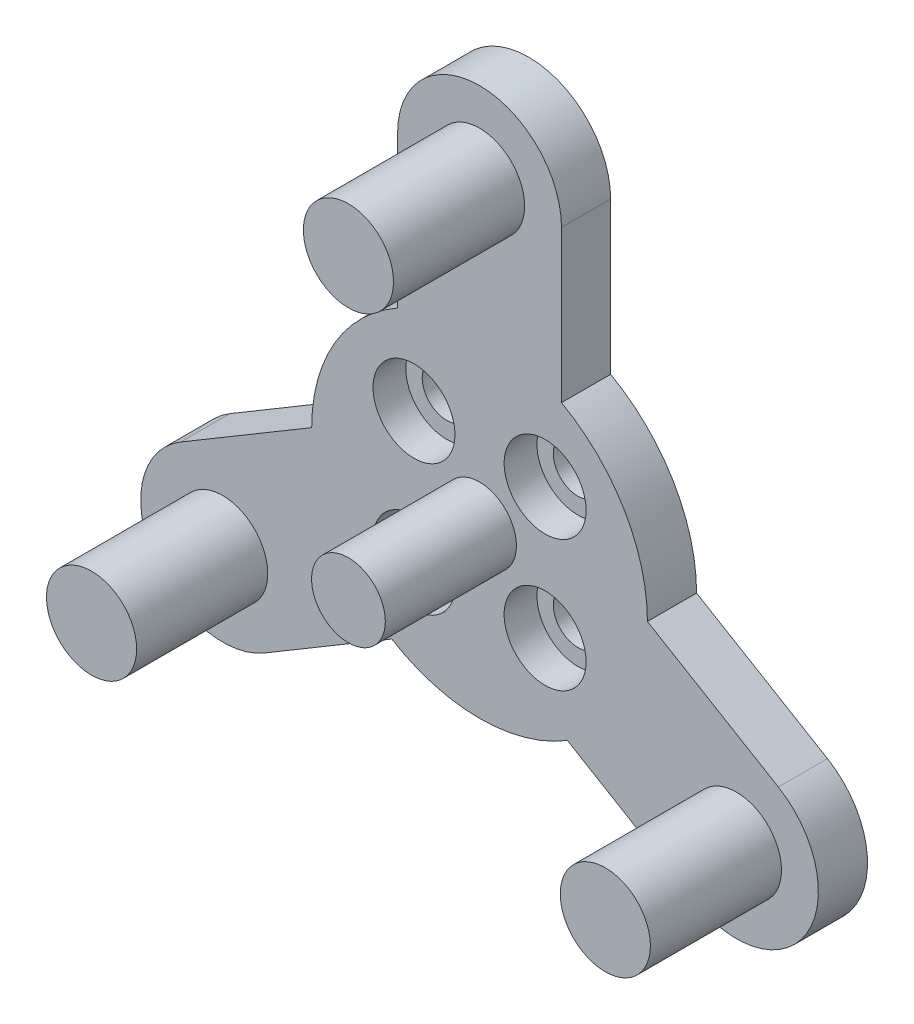
SolidWorks part; units mm, degrees
ref_plane "Alzado" through (0, 0, 0) normal (0, 0, 1) x (1, 0, 0)
ref_plane "Planta" through (0, 0, 0) normal (0, 1, 0) x (1, 0, 0)
ref_plane "Vista lateral" through (0, 0, 0) normal (1, 0, 0) x (0, 0, -1)
sketch "Croquis1" plane through (0, 0, 0) normal (0, 0, 1) x (1, 0, 0)
  line L0 (-18.2318, -4.7531) -> (-10.2435, 0)
  line L1 (-13.1183, -13.3469) -> (-5.359, -8.7299)
  line L2 (13.1183, -13.3469) -> (5.359, -8.7299)
  line L3 (-13.1183, -13.3469) -> (-18.2318, -4.7531)
  line L7 (13.1183, -13.3469) -> (18.2318, -4.7531)
  line L11 (-5, 18.2) -> (5, 18.2)
  line L15 (18.2318, -4.7531) -> (10.2435, 0)
  line L16 (-5, 18.2) -> (-5, 8.9404)
  line L17 (5, 18.2) -> (5, 8.9404)
  circle A0 centre (0, 18.2) radius 5
  circle A1 centre (15.6751, -9.05) radius 5
  circle A2 centre (-15.6751, -9.05) radius 5
  circle A3 centre (0, 0) radius 10.2435
  dimension "D7" = 10
  dimension "D8" = 10
  dimension "D9" = 10
  dimension "D1" = 90
  dimension "D2" = 90
  dimension "D3" = 90
  dimension "D4" = 18.1
  dimension "D5" = 18.1
  dimension "D6" = 18.2
  dimension "D10" = 90
  dimension "D11" = 90
  dimension "D12" = 90
extrude "Saliente-Extruir1" add sketch "Croquis1" along normal blind 3 contours L3 A2 | L3 A2 | A3 L0 A2 L1 | A3 | A3 L2 A1 L15 | A3 L17 A0 L16 | L11 A0 | L11 A0
sketch "Croquis2" plane through (0, 0, 3) normal (0, 0, 1) x (1, 0, 0)
  circle A0 centre (0, 18.2) radius 2.75
  circle A1 centre (15.6751, -9.05) radius 2.75
  circle A2 centre (-15.6751, -9.05) radius 2.75
  dimension "D1" = 5.5
  dimension "D2" = 5.5
  dimension "D3" = 5.5
extrude "Saliente-Extruir2" add sketch "Croquis2" along normal blind 8
sketch "Croquis3" plane through (0, 0, 3) normal (0, 0, 1) x (1, 0, 0)
  circle A0 centre (0, 0) radius 2.25
  dimension "D1" = 4.5
extrude "Saliente-Extruir3" add sketch "Croquis3" along normal blind 8
sketch "Croquis4" plane through (0, 0, 0) normal (0, 0, -1) x (-1, 0, 0)
  line L1 (-4, 4) -> (4, 4)
  line L2 (-4, 4) -> (-4, -4)
  line L3 (-4, -4) -> (4, -4)
  line L4 (4, 4) -> (4, -4)
  line L5 (-4, 4) -> (4, -4) construction
  line L6 (-4, -4) -> (4, 4) construction
  circle A0 centre (-4, 4) radius 1.5
  circle A1 centre (4, 4) radius 1.5
  circle A2 centre (4, -4) radius 1.5
  circle A3 centre (-4, -4) radius 1.5
  circle A4 centre (0, 0) radius 0.5844
  point P0 (0, 0)
  dimension "D3" = 3
  dimension "D4" = 3
  dimension "D5" = 3
  dimension "D6" = 3
  dimension "D1" = 8
  dimension "D2" = 8
extrude "Cortar-Extruir1" cut sketch "Croquis4" against normal blind 10 contours L1 A0 L2 | L2 A0 L1 | L1 A1 L4 | L4 A1 L1 | L4 A2 L3 | L2 A3 L3 | L3 A3 L2
sketch "Croquis5" plane through (0, 0, 3) normal (0, 0, 1) x (1, 0, 0)
  circle A0 centre (-4, 4) radius 2.5
  circle A1 centre (4, 4) radius 2.5
  circle A2 centre (4, -4) radius 2.5
  circle A3 centre (-4, -4) radius 2.5
  dimension "D1" = 5
  dimension "D2" = 5
  dimension "D3" = 5
  dimension "D4" = 5
extrude "Cortar-Extruir2" cut sketch "Croquis5" against normal blind 2
